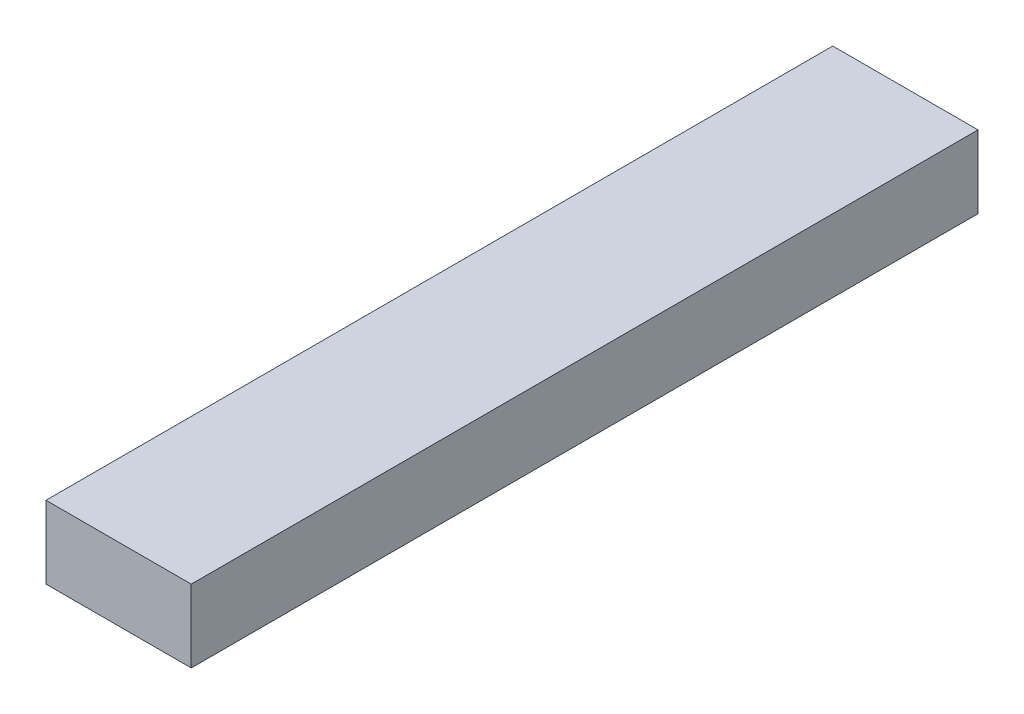
SolidWorks part; units mm, degrees
material "Sapin"
ref_plane "Plan de face" through (0, 0, 0) normal (0, 0, 1) x (1, 0, 0)
ref_plane "Plan de dessus" through (0, 0, 0) normal (0, 1, 0) x (1, 0, 0)
ref_plane "Plan de droite" through (0, 0, 0) normal (1, 0, 0) x (0, 0, -1)
sketch "Esquisse1" plane through (0, 0, 0) normal (0, 1, 0) x (1, 0, 0)
  line L1 (-24, -130) -> (24, -130)
  line L2 (-24, -130) -> (-24, 130)
  line L3 (-24, 130) -> (24, 130)
  line L4 (24, -130) -> (24, 130)
  line L5 (-24, -130) -> (24, 130) construction
  line L6 (-24, 130) -> (24, -130) construction
  point P0 (0, 0)
  dimension "D1" = 260
  dimension "D2" = 48
extrude "Boss.-Extru.1" add sketch "Esquisse1" along normal blind 24
sketch "Esquisse2" plane through (24, 0, 0) normal (1, 0, 0) x (0, 0, -1)
  line L0 (0, 0) -> (0, 61.5655) construction
  line L1 (130, 24) -> (130, 0) construction
  line L2 (-130, 0) -> (130, 0) construction
  circle A0 centre (-113, 12) radius 4
  circle A2 centre (113, 12) radius 4
  dimension "D4" = 8
  dimension "D2" = 17
  dimension "D3" = 12
extrude "Enlèv. mat.-Extru.1" [suppressed] cut sketch "Esquisse2" against normal through all
sketch "Esquisse3" [suppressed] plane through (24, 0, 0) normal (1, 0, 0) x (0, 0, -1)
  circle A0 centre (-83, 12) radius 9
  circle A2 centre (83, 12) radius 9
  dimension "D1" = 18
extrude "Enlèv. mat.-Extru.2" [suppressed] cut sketch "Esquisse3" against normal blind 12
sketch "Esquisse4" [suppressed] plane through (-24, 0, 0) normal (-1, 0, 0) x (0, 0, 1)
  circle A0 centre (-83, 12) radius 6
  circle A2 centre (83, 12) radius 6
  dimension "D1" = 12
extrude "Enlèv. mat.-Extru.3" [suppressed] cut sketch "Esquisse4" against normal blind 8
